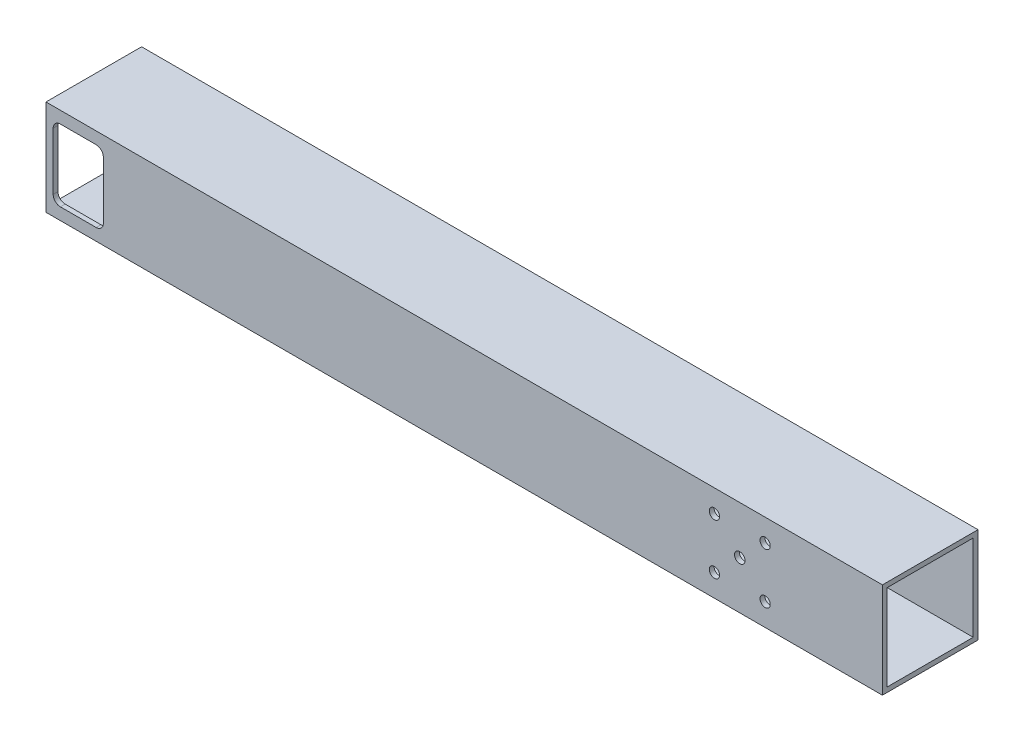
SolidWorks part; units mm, degrees
material "6061-T6 (SS)"
ref_plane "Front Plane" through (0, 0, 0) normal (0, 0, 1) x (1, 0, 0)
ref_plane "Top Plane" through (0, 0, 0) normal (0, 1, 0) x (1, 0, 0)
ref_plane "Right Plane" through (0, 0, 0) normal (1, 0, 0) x (0, 0, -1)
sketch "Sketch1" plane through (0, 0, 0) normal (1, 0, 0) x (0, 0, -1)
  line L0 (2, 2) -> (2, 38)
  line L1 (0, 0) -> (40, 0)
  line L2 (0, 0) -> (0, 40)
  line L3 (0, 40) -> (40, 40)
  line L4 (40, 0) -> (40, 40)
  line L5 (2, 38) -> (38, 38)
  line L6 (38, 2) -> (38, 38)
  line L7 (2, 2) -> (38, 2)
  dimension "D1" = 40
  dimension "D2" = 2
extrude "Boss-Extrude1" add sketch "Sketch1" along normal blind 350
sketch "Sketch2" plane through (0, 0, 0) normal (0, 0, 1) x (1, 0, 0)
  line L0 (350, 20) -> (290.313, 20) construction
  line L1 (350, 40) -> (350, 0) construction
  line L2 (290.313, 20) -> (300.9196, 30.6066)
  circle A0 centre (290.313, 20) radius 15 construction
  point P13 (300.9196, 30.6066)
  point P25 (300.9196, 9.3934)
  point P26 (279.7064, 9.3934)
  point P27 (279.7064, 30.6066)
  dimension "D1" = 30
  dimension "D2" = 4
hole_wizard "M4 Clearance Hole1" positions "Sketch2" profile "Sketch4" hole size "M4" standard "DIN"
sketch "Sketch4" plane through (279.7064, 30.6066, 0) normal (1, 0, 0) x (0, -1, 0)
  line L0 (0, 0) -> (0, 3.2919)
  line L1 (0, 3.2919) -> (2.15, 2)
  line L2 (2.15, 2) -> (2.15, 0)
  line L5 (2.15, 0) -> (0, 0)
  line L10 (0, 3.2919) -> (-2.15, 2) construction
  line L11 (0, -6.35) -> (0, 107.95) construction
  dimension "Hole Dia." = 4.3
  dimension "Hole Depth" = 2
  dimension "Drill Angle" = 118
sketch "Sketch5" plane through (0, 0, -40) normal (0, 0, -1) x (-1, 0, 0)
  line L0 (-350, 38) -> (0, 38) construction
  line L1 (-272.313, 2) -> (-308.313, 2) construction
  line L2 (-272.313, 2) -> (-272.313, 38) construction
  line L3 (-272.313, 38) -> (-308.313, 38) construction
  line L4 (-308.313, 2) -> (-308.313, 38) construction
  line L5 (-272.313, 2) -> (-308.313, 38) construction
  line L6 (-272.313, 38) -> (-308.313, 2) construction
  line L7 (-350, 38) -> (0, 38) construction
  line L8 (-350, 2) -> (0, 2) construction
  line L9 (-350, 2) -> (0, 2) construction
  line L10 (-272.813, 2.5) -> (-272.813, 37.5)
  line L11 (-272.813, 37.5) -> (-307.813, 37.5)
  line L12 (-307.813, 2.5) -> (-307.813, 37.5)
  line L13 (-272.813, 2.5) -> (-307.813, 2.5)
  circle A0 centre (-300.9196, 9.3934) radius 2.15 construction
  circle A1 centre (-279.7064, 9.3934) radius 2.15 construction
  circle A2 centre (-300.9196, 30.6066) radius 2.15 construction
  circle A3 centre (-279.7064, 30.6066) radius 2.15 construction
  circle A4 centre (-300.9196, 9.3934) radius 2.15 construction
  circle A5 centre (-279.7064, 9.3934) radius 2.15 construction
  circle A6 centre (-300.9196, 30.6066) radius 2.15 construction
  circle A7 centre (-279.7064, 30.6066) radius 2.15 construction
  circle A8 centre (-290.313, 20) radius 15 construction
  dimension "D1" = 0.5
extrude "Cut-Extrude1" cut sketch "Sketch5" against normal up to surface (2 mm away) up to face at (175, 20, -38)
sketch "Sketch8" plane through (0, 0, -2) normal (0, 0, -1) x (-1, 0, 0)
  circle A0 centre (-290.313, 20) radius 15
  point P1 (-290.313, 20)
  point P7 (-300.9196, 9.3934)
  point P10 (-300.9196, 30.6066)
hole_wizard "Ø4.4 (4.4) Diameter Hole1" positions "Sketch8" profile "Sketch7" hole size "Ø4.4" standard "DIN"
sketch "Sketch7" plane through (290.313, 20, -2) normal (1, 0, 0) x (0, 1, 0)
  line L0 (0, 0) -> (0, 2)
  line L1 (0, 2) -> (2.2, 2)
  line L2 (2.2, 2) -> (2.2, 0)
  line L5 (2.2, 0) -> (0, 0)
  line L11 (0, -6.35) -> (0, 107.95) construction
  dimension "Thru Hole Dia." = 4.4
  dimension "Thru Hole Depth" = 2
sketch "Sketch9" plane through (0, 0, -38) normal (0, 0, 1) x (1, 0, 0)
  circle A6 centre (20.25, 9) radius 2.75
  circle A7 centre (13.5, 9) radius 2.75
  circle A8 centre (6.75, 9) radius 2.75
  circle A9 centre (20.25, 31) radius 2.75
  circle A10 centre (13.5, 31) radius 2.75
  circle A11 centre (6.75, 31) radius 2.75
  point P3 (20.25, 31)
  point P5 (13.5, 31)
  point P7 (6.75, 31)
  point P9 (20.25, 9)
  point P11 (13.5, 9)
  point P18 (6.75, 9)
hole_wizard "M3 Clearance Hole1" positions "Sketch9" profile "Sketch10" hole size "M3" standard "DIN"
sketch "Sketch10" plane through (6.75, 9, -38) normal (1, 0, 0) x (0, -1, 0)
  line L0 (0, 0) -> (0, 21.0215)
  line L1 (0, 21.0215) -> (1.7, 20)
  line L2 (1.7, 20) -> (1.7, 0)
  line L5 (1.7, 0) -> (0, 0)
  line L10 (0, 21.0215) -> (-1.7, 20) construction
  line L11 (0, -6.35) -> (0, 107.95) construction
  dimension "Hole Dia." = 3.4
  dimension "Hole Depth" = 20
  dimension "Drill Angle" = 118
sketch "Sketch11" plane through (0, 0, 0) normal (0, 0, 1) x (1, 0, 0)
  line L0 (0, 40) -> (0, 0) construction
  line L1 (6, 35) -> (21, 35)
  line L2 (3, 32) -> (3, 8)
  line L3 (6, 5) -> (21, 5)
  line L4 (24, 32) -> (24, 8)
  line L5 (350, 40) -> (0, 40) construction
  line L6 (350, 0) -> (0, 0) construction
  arc A0 (24, 32) -> (21, 35) centre (21, 32) ccw
  arc A1 (21, 5) -> (24, 8) centre (21, 8) ccw
  arc A2 (6, 5) -> (3, 8) centre (6, 8) cw
  arc A3 (3, 32) -> (6, 35) centre (6, 32) cw
  point P14 (24, 5)
  point P17 (3, 5)
  dimension "D5" = 3
  dimension "D1" = 3
  dimension "D2" = 5
  dimension "D3" = 5
  dimension "D4" = 21
extrude "Cut-Extrude2" cut sketch "Sketch11" against normal up to next and the other way through all
